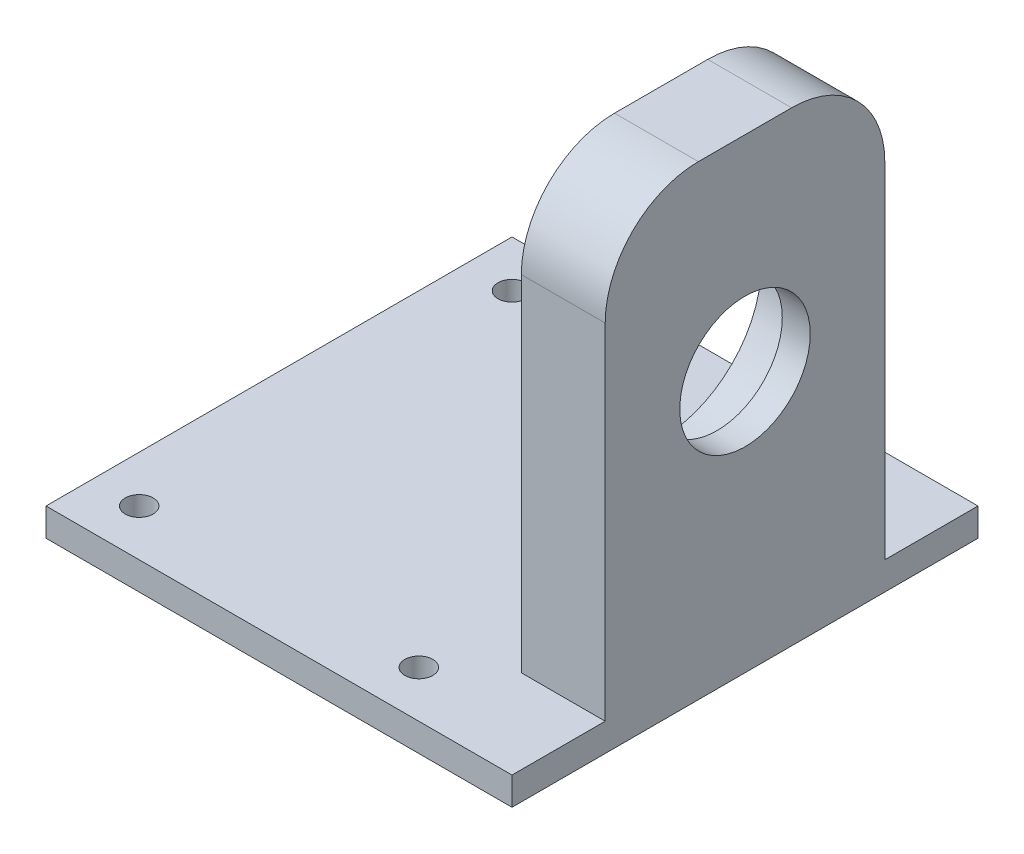
SolidWorks part; units mm, degrees
material "ABS"
ref_plane "Plan de face" through (0, 0, 0) normal (0, 0, 1) x (1, 0, 0)
ref_plane "Plan de dessus" through (0, 0, 0) normal (0, 1, 0) x (1, 0, 0)
ref_plane "Plan de droite" through (0, 0, 0) normal (1, 0, 0) x (0, 0, -1)
sketch "Esquisse1" plane through (0, 0, 0) normal (0, 1, 0) x (1, 0, 0)
  line L1 (0, 0) -> (50, 0)
  line L2 (0, 0) -> (0, 50)
  line L3 (0, 50) -> (50, 50)
  line L4 (50, 0) -> (50, 50)
  dimension "D1" = 50
  dimension "D2" = 50
extrude "Boss.-Extru.1" add sketch "Esquisse1" along normal blind 3
sketch "Esquisse2" plane through (0, 3, 0) normal (0, 1, 0) x (1, 0, 0)
  line L0 (50, 40) -> (41, 40)
  line L1 (50, 0) -> (50, 50) construction
  line L2 (41, 40) -> (41, 10)
  line L3 (41, 10) -> (50, 10)
  line L4 (50, 50) -> (0, 50) construction
  line L5 (50, 40) -> (50, 10)
  dimension "D1" = 9
  dimension "D2" = 30
  dimension "D3" = 10
extrude "Boss.-Extru.2" add sketch "Esquisse2" along normal blind 47
sketch "Esquisse3" plane through (50, 0, 0) normal (1, 0, 0) x (0, 0, -1)
  line L0 (25, 0) -> (25, 28) construction
  line L1 (0, 0) -> (50, 0) construction
  line L2 (40, 50) -> (40, 3) construction
  circle A0 centre (25, 28) radius 7
  dimension "D2" = 14
  dimension "D1" = 28
  dimension "D3" = 15
extrude "Enlèv. mat.-Extru.2" cut sketch "Esquisse3" against normal blind 3
sketch "Esquisse4" plane through (47, 0, 0) normal (1, 0, 0) x (0, 0, -1)
  circle A0 centre (25, 28) radius 10.75
  circle A1 centre (25, 28) radius 7 construction
  dimension "D1" = 0
  dimension "D2" = 21.5
extrude "Enlèv. mat.-Extru.3" cut sketch "Esquisse4" against normal up to next
fillet "Congé1" radius 10 2 edges at (45.5, 50, -10) (45.5, 50, -40)
sketch "Esquisse5" plane through (0, 3, 0) normal (0, 1, 0) x (1, 0, 0)
  circle A0 centre (35, 45) radius 1.5
  circle A1 centre (5, 45) radius 1.5
  circle A2 centre (5, 5) radius 1.5
  circle A3 centre (35, 5) radius 1.5
  point P5 (35, 25)
  point P11 (5, 25)
  dimension "D5" = 3
  dimension "D6" = 3
  dimension "D7" = 3
  dimension "D8" = 3
  dimension "D3" = 40
  dimension "D4" = 40
extrude "Enlèv. mat.-Extru.4" cut sketch "Esquisse5" against normal up to next
